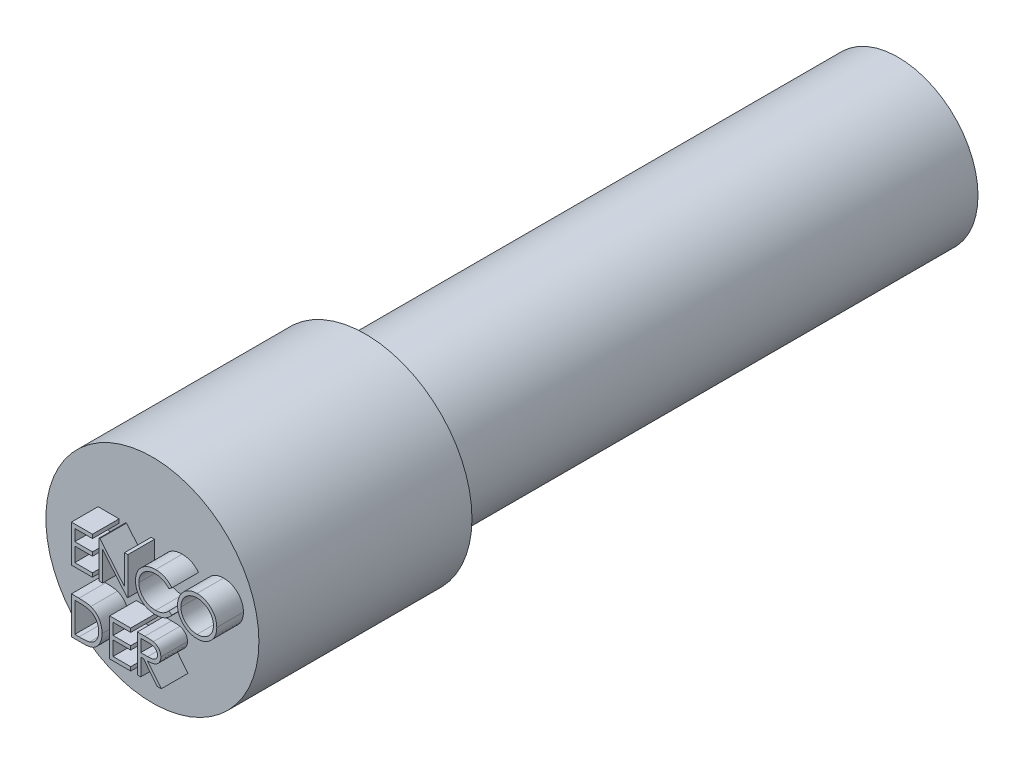
SolidWorks part; units mm, degrees
ref_plane "Front Plane" through (0, 0, 0) normal (0, 0, 1) x (1, 0, 0)
ref_plane "Top Plane" through (0, 0, 0) normal (0, 1, 0) x (1, 0, 0)
ref_plane "Right Plane" through (0, 0, 0) normal (1, 0, 0) x (0, 0, -1)
sketch "Sketch1" plane through (0, 0, 0) normal (0, 0, 1) x (1, 0, 0)
  circle A0 centre (0, 2.2693) radius 1.5
extrude "Boss-Extrude1" add sketch "Sketch1" along normal blind 10
sketch "Sketch2" plane through (0, 0, 10) normal (0, 0, 1) x (1, 0, 0)
  circle A0 centre (0, 2.2693) radius 2
  circle A1 centre (0, 2.2693) radius 1.5 construction
  dimension "D1" = 0
extrude "Boss-Extrude2" add sketch "Sketch2" along normal blind 4
sketch "Sketch3" plane through (0, 0, 14) normal (0, 0, 1) x (1, 0, 0)
  text T0 "ENCO\r\nDER" font "Century Gothic" height 0.7
  point P1 (0, 0)
  point P2 (-1.1091, 2.2514)
  point P3 (0, 0)
extrude "Boss-Extrude3" add sketch "Sketch3" along normal blind 0.5
